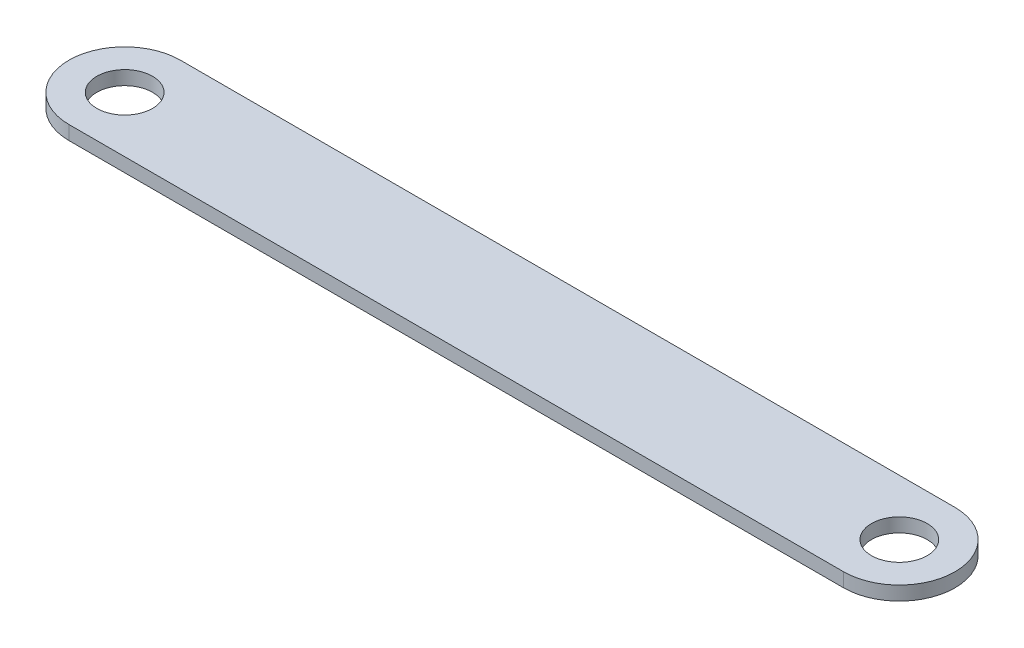
SolidWorks part; units mm, degrees
ref_plane "Front Plane" through (0, 0, 0) normal (0, 0, 1) x (1, 0, 0)
ref_plane "Top Plane" through (0, 0, 0) normal (0, 1, 0) x (1, 0, 0)
ref_plane "Right Plane" through (0, 0, 0) normal (1, 0, 0) x (0, 0, -1)
sketch "Sketch1" plane through (0, 0, 0) normal (0, 1, 0) x (1, 0, 0)
  line L0 (0, 0) -> (176.5478, 0) construction
  line L1 (0, 12.7) -> (176.5478, 12.7)
  line L2 (0, -12.7) -> (176.5478, -12.7)
  arc A0 (0, 12.7) -> (0, -12.7) centre (0, 0) ccw
  arc A1 (176.5478, -12.7) -> (176.5478, 12.7) centre (176.5478, 0) ccw
  circle A2 centre (0, 0) radius 6.35
  circle A3 centre (176.5478, 0) radius 6.35
  point P3 (88.2739, 0)
  dimension "D2" = 12.7
  dimension "D3" = 12.7
  dimension "D4" = 12.7
  dimension "D1" = 176.5478
extrude "Boss-Extrude1" add sketch "Sketch1" along normal blind 3.175
